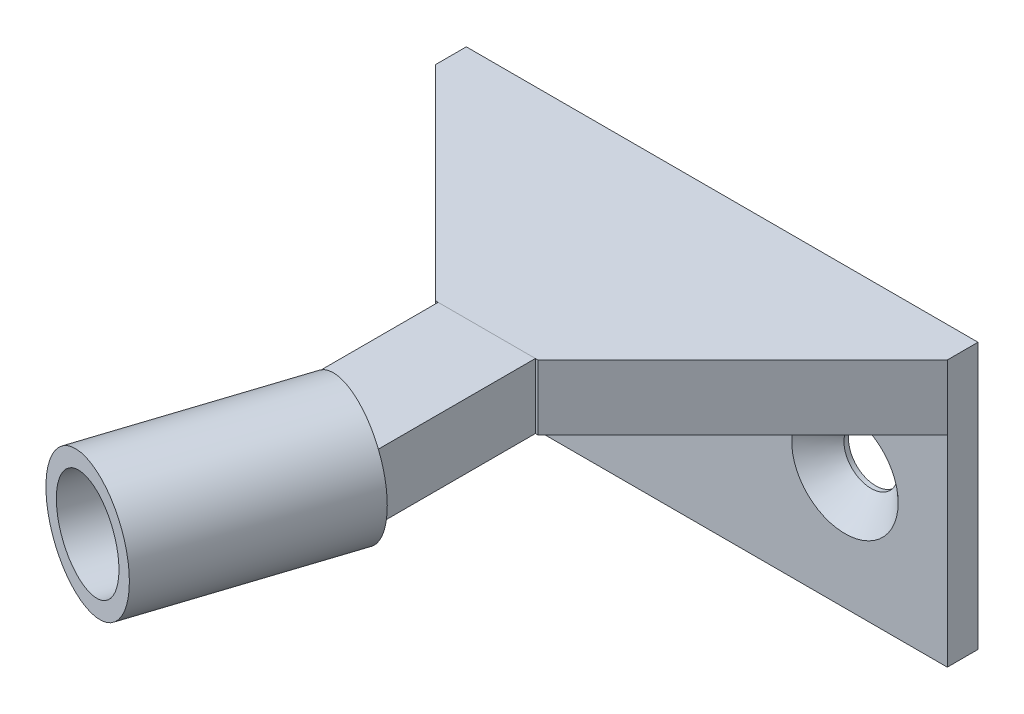
SolidWorks part; units mm, degrees
material "Ti-3Al-8V-6Cr-4Mo-4Zr (SS)"
ref_plane "Top Plane" through (0, 0, 0) normal (0, 0, 1) x (1, 0, 0)
ref_plane "Front Plane" through (0, 0, 0) normal (0, 1, 0) x (1, 0, 0)
ref_plane "Right Plane" through (0, 0, 0) normal (1, 0, 0) x (0, 0, -1)
sketch "Base" plane through (0, 0, 0) normal (0, 0, 1) x (1, 0, 0)
  line L1 (-25, -13) -> (25, -13)
  line L2 (-25, -13) -> (-25, 13)
  line L3 (-25, 13) -> (25, 13)
  line L4 (25, -13) -> (25, 13)
  line L5 (-25, -13) -> (25, 13) construction
  line L6 (-25, 13) -> (25, -13) construction
  point P0 (0, 0)
  dimension "D1" = 50
  dimension "D2" = 26
extrude "Boss-Extrude2" add sketch "Base" along normal blind 3 separate body
ref_plane "Plane2" through (0, 0, 0) normal (0.309, 0, -0.9511) x (-0.9511, 0, -0.309)
ref_plane "Plane3" through (-16.9959, 0, 52.3081) normal (-0.309, 0, 0.9511) x (0.9511, 0, 0.309)
sketch "Sketch2" plane through (-16.9959, 0, 52.3081) normal (-0.309, 0, 0.9511) x (0.9511, 0, 0.309)
  line L1 (23.7764, -13) -> (23.7764, 13) construction
  line L2 (-23.7764, 13) -> (23.7764, 13) construction
  circle A0 centre (11.3714, 9.08) radius 6.35
  dimension "D1" = 12.7
  dimension "D2" = 12.405
  dimension "D3" = 3.92
extrude "Boss-Extrude1" add sketch "Sketch2" against normal blind 20
sketch "Sketch7" plane through (-16.9959, 0, 52.3081) normal (-0.309, 0, 0.9511) x (0.9511, 0, 0.309)
  circle A0 centre (11.3714, 9.08) radius 4.7625
  dimension "D1" = 9.525
extrude "Cut-Extrude1" cut sketch "Sketch7" against normal blind 15
sketch "Sketch5" plane through (0, 0, 3) normal (0, 0, 1) x (1, 0, 0)
  line L0 (25, -13) -> (25, 13) construction
  line L1 (-25, 13) -> (25, 13)
  line L2 (-25, 13) -> (-25, 6.65)
  line L3 (-25, 6.65) -> (25, 6.65)
  line L4 (25, 13) -> (25, 6.65)
  dimension "D1" = 6.35
ref_plane "Plane6" through (0, 0, 23) normal (0, 0, 1) x (1, 0, 0)
sketch "Sketch6" plane through (0, 0, 23) normal (0, 0, 1) x (1, 0, 0)
  line L0 (-25, 13) -> (25, 13) construction
  line L1 (-5, 13) -> (5, 13)
  line L2 (-5, 13) -> (-5, 6.65)
  line L3 (-5, 6.65) -> (5, 6.65)
  line L4 (5, 13) -> (5, 6.65)
  line L6 (-25, 13) -> (25, 13)
  point P6 (0, 13)
  point P7 (0, 13)
  dimension "D1" = 10
  dimension "D2" = 6.35
loft "Loft2" add profiles "Sketch5" section "Sketch6" section "Sketch5"
sketch "Sketch17" plane through (0, 0, 23) normal (0, 0, 1) x (1, 0, 0)
  line L0 (-5, 13) -> (5, 13) construction
  line L8 (-4.7515, 13.0005) -> (-4.7515, 6.6471)
  line L9 (-4.7515, 6.6471) -> (4.7504, 6.6471)
  line L10 (4.7504, 6.6471) -> (4.7504, 13)
  line L11 (4.7504, 13) -> (-4.7515, 13.0005)
  ellipse E0 centre (-0.0007, 9.08) end of major axis (-0.0007, 15.43) minor radius 6.0392 construction
  point P2 (0, 0)
  point P4 (0, 0)
  point P6 (4.7504, 13)
  point P15 (-4.7475, 13)
extrude "Boss-Extrude8" add sketch "Sketch17" along normal up to body
sketch "Sketch10" plane through (0, 0, 3) normal (0, 0, 1) x (1, 0, 0)
  line L0 (-25, 6.65) -> (-25, -13) construction
  line L1 (25, -13) -> (25, 6.65) construction
  line L2 (-25, -13) -> (25, -13) construction
  point P0 (-15, -1.5)
  point P2 (15, -1.5)
  dimension "D1" = 10
  dimension "D2" = 10
  dimension "D3" = 30
  dimension "D4" = 11.5
hole_wizard "CSK for M5 Flat Head Machine Screw2" positions "Sketch10" profile "Sketch11" countersink size "M5" standard "ANSI Metric"
sketch "Sketch11" plane through (-15, -1.5, 3) normal (1, 0, 0) x (0, -1, 0)
  line L0 (0, 0) -> (0, 11.5923)
  line L1 (0, 11.5923) -> (2.65, 10)
  line L2 (2.65, 10) -> (2.65, 2.55)
  line L3 (2.65, 2.55) -> (5.2, 0)
  line L5 (5.2, 0) -> (0, 0)
  line L6 (-2.65, 2.55) -> (-5.2, 0) construction
  line L10 (0, 11.5923) -> (-2.65, 10) construction
  line L11 (0, -6.35) -> (0, 107.95) construction
  dimension "Hole Dia." = 5.3
  dimension "Hole Depth" = 10
  dimension "Near C'Sink Dia." = 10.4
  dimension "Near C'Sink Angle" = 90
  dimension "Drill Angle" = 118
